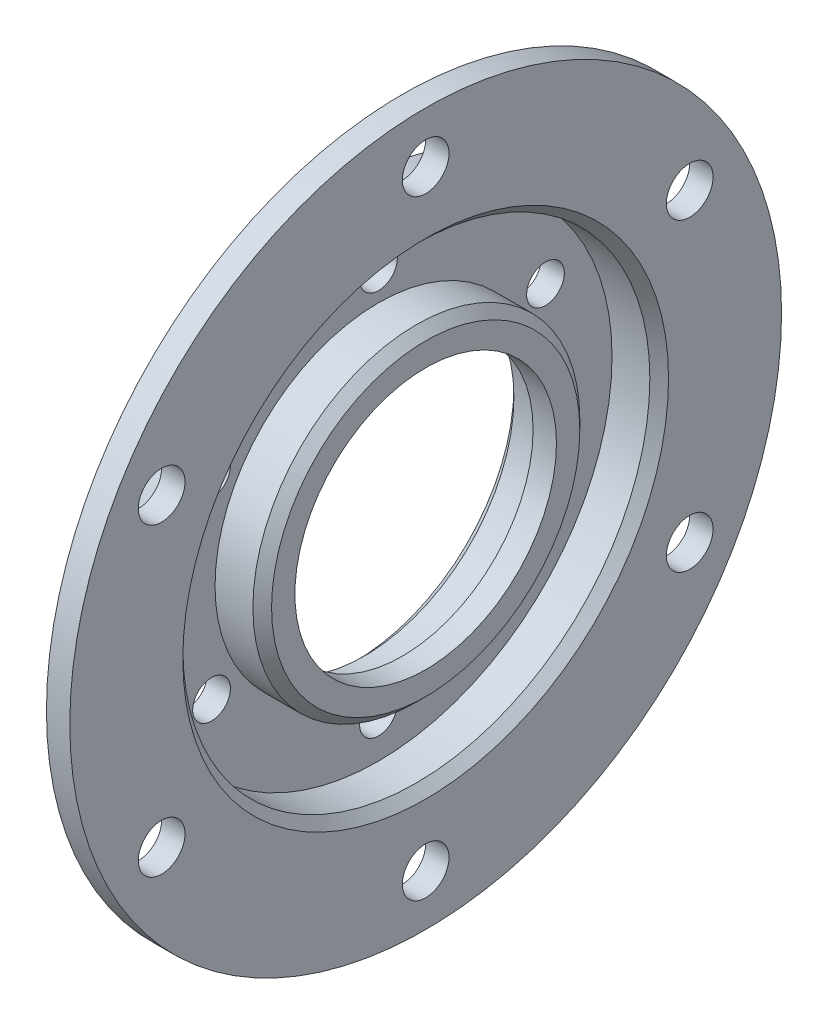
SolidWorks part; units mm, degrees
material "6061-T6 (SS)"
ref_plane "Front Plane" through (0, 0, 0) normal (0, 0, 1) x (1, 0, 0)
ref_plane "Top Plane" through (0, 0, 0) normal (0, 1, 0) x (1, 0, 0)
ref_plane "Right Plane" through (0, 0, 0) normal (1, 0, 0) x (0, 0, -1)
sketch "Sketch1" plane through (0, 0, 0) normal (1, 0, 0) x (0, 0, -1)
  line L0 (0, 0) -> (0, 20.64) construction
  arc A0 (-1.6237, 23.2194) -> (1.6237, -23.2194) centre (0, 0) ccw construction
  arc A1 (1.0588, 18.9205) -> (-1.0588, 22.3595) centre (0, 20.64) ccw construction
  circle A2 centre (0, 0) radius 27.5
  circle A3 centre (0, 20.64) radius 2.0193
  circle A4 centre (17.8748, 10.32) radius 2.0193
  circle A5 centre (17.8748, -10.32) radius 2.0193
  circle A6 centre (0, -20.64) radius 2.0193
  circle A7 centre (-17.8748, -10.32) radius 2.0193
  circle A8 centre (-17.8748, 10.32) radius 2.0193
  circle A9 centre (0, 0) radius 17.46 construction
  circle A10 centre (0, 0) radius 16
  point P21 (0, 0)
  dimension "D1" = 23.2761
  dimension "D2" = 2.0193
  dimension "D3" = 20.64
  dimension "D5" = 34.92
  dimension "D6" = 55
  dimension "D7" = 32
  dimension "D4" = 6
extrude "Boss-Extrude1" add sketch "Sketch1" along normal blind 5.05
sketch "Sketch2" plane through (5.05, 0, 0) normal (1, 0, 0) x (0, 0, -1)
  line L0 (0, 0) -> (0, 32.64) construction
  circle A0 centre (0, 0) radius 38.1
  circle A1 centre (0, 20.64) radius 2.0193
  circle A2 centre (0, 20.64) radius 2.0193
  circle A3 centre (0, 0) radius 14
  circle A5 centre (17.8748, 10.32) radius 2.0193
  circle A6 centre (17.8748, 10.32) radius 2.0193
  circle A7 centre (17.8748, -10.32) radius 2.0193
  circle A8 centre (17.8748, -10.32) radius 2.0193
  circle A9 centre (0, -20.64) radius 2.0193
  circle A10 centre (0, -20.64) radius 2.0193
  circle A11 centre (-17.8748, -10.32) radius 2.0193
  circle A12 centre (-17.8748, -10.32) radius 2.0193
  circle A13 centre (-17.8748, 10.32) radius 2.0193
  circle A14 centre (-17.8748, 10.32) radius 2.0193
  circle A15 centre (0, 0) radius 32.64 construction
  circle A16 centre (0, 32.64) radius 2.5
  circle A17 centre (28.2671, 16.32) radius 2.5
  circle A18 centre (28.2671, -16.32) radius 2.5
  circle A19 centre (0, -32.64) radius 2.5
  circle A20 centre (-28.2671, -16.32) radius 2.5
  circle A21 centre (-28.2671, 16.32) radius 2.5
  point P37 (0, 0)
  dimension "D2" = 76.2
  dimension "D8" = 28
  dimension "D9" = 65.28
  dimension "D10" = 5
  dimension "D1" = 0
  dimension "D3" = 0
  dimension "D4" = 0
  dimension "D5" = 0
  dimension "D6" = 0
  dimension "D7" = 0
  dimension "D11" = 6
extrude "Boss-Extrude2" add sketch "Sketch2" along normal blind 2.5
sketch "Sketch3" plane through (7.55, 0, 0) normal (1, 0, 0) x (0, 0, -1)
  circle A0 centre (0, 0) radius 25
  circle A1 centre (0, 0) radius 17.5
  dimension "D1" = 35
  dimension "D2" = 50
extrude "Cut-Extrude1" cut sketch "Sketch3" against normal offset from surface (5.05 mm away) 2.5 up to face at (0, 0, -27.5)
chamfer "Chamfer1" distance 1 angle 45 4 edges at (7.55, 0, -17.5) (7.55, 0, -25) (0, 0, -16) (5.05, 0, -27.5)
